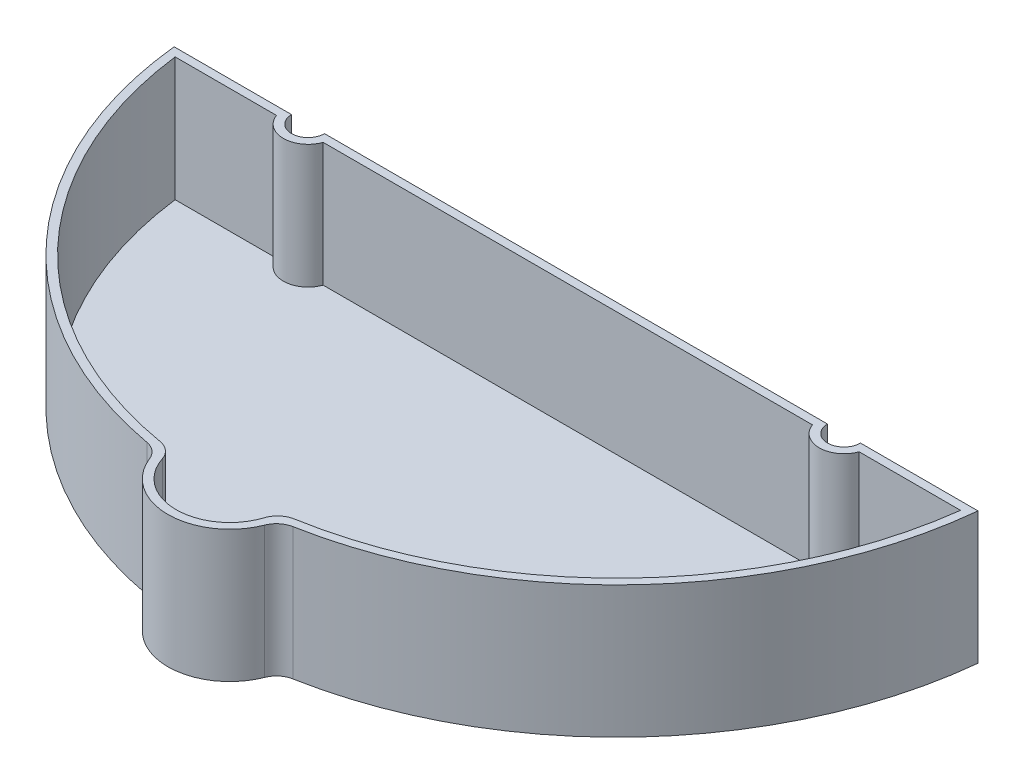
SolidWorks part; units mm, degrees
ref_plane "前视基准面" through (0, 0, 0) normal (0, 0, 1) x (1, 0, 0)
ref_plane "上视基准面" through (0, 0, 0) normal (0, 1, 0) x (1, 0, 0)
ref_plane "右视基准面" through (0, 0, 0) normal (1, 0, 0) x (0, 0, -1)
sketch "草图1" plane through (0, 0, 0) normal (0, 1, 0) x (1, 0, 0)
  line L0 (0, 0) -> (0, 54.022) construction
  line L1 (-97.4885, 50) -> (-69, 50)
  line L5 (-61, 50) -> (-7.5, 50)
  line L8 (7.5, 50) -> (61, 50)
  line L9 (69, 50) -> (97.4885, 50)
  line L10 (-7.5, 50) -> (7.5, 50)
  arc A2 (-97.4885, 50) -> (-14.7193, -36.8883) centre (0, 60) ccw
  arc A4 (-69, 50) -> (-61, 50) centre (-65, 50) ccw
  arc A6 (69, 50) -> (61, 50) centre (65, 50) cw
  arc A8 (-14.7193, -36.8883) -> (14.7193, -36.8883) centre (0, -34) ccw
  arc A9 (14.7193, -36.8883) -> (97.4885, 50) centre (0, 60) ccw
  point P1 (0, 0)
  dimension "D3" = 8
  dimension "D4" = 65
  dimension "D1" = 98
  dimension "D5" = 30
  dimension "D2" = 0
  dimension "D6" = 84
  dimension "D7" = 60
  dimension "D8" = 10
extrude "凸台-拉伸1" add sketch "草图1" along normal blind 32 from offset 2 offset against normal yes
shell "抽壳1" thickness 2
fillet "圆角1" radius 5 4 edges at (14.7193, 14, 36.8883) (-14.7193, 14, 36.8883) (12.9515, 15, 35.1223) (-12.9515, 15, 35.1223)
sketch "草图2" plane through (0, 30, 0) normal (0, 1, 0) x (1, 0, 0)
  line L0 (-97.4885, 50) -> (-69, 50)
  line L1 (-61, 50) -> (61, 50)
  line L2 (69, 50) -> (97.4885, 50)
  line L6 (63.0793, -15) -> (-63.0793, -15)
  line L7 (-69, 50) -> (-97.4885, 50) construction
  line L8 (0, 48) -> (0, -59.8527) construction
  line L9 (97.4885, 50) -> (69, 50) construction
  line L10 (61, 50) -> (-61, 50) construction
  arc A1 (-97.4885, 50) -> (-17.7151, -36.3856) centre (0, 60) ccw construction
  arc A2 (63.0793, -15) -> (97.4885, 50) centre (0, 60) ccw
  circle A8 centre (60.6593, 21.3431) radius 2.5
  arc A9 (-97.4885, 50) -> (-63.0793, -15) centre (0, 60) ccw
  arc A12 (61, 50) -> (69, 50) centre (65, 50) ccw
  arc A13 (-69, 50) -> (-61, 50) centre (-65, 50) ccw
  arc A15 (17.7151, -36.3856) -> (97.4885, 50) centre (0, 60) ccw construction
  arc A16 (-69, 50) -> (-61, 50) centre (-65, 50) ccw construction
  arc A17 (61, 50) -> (69, 50) centre (65, 50) ccw construction
  dimension "D2" = 5
  dimension "D1" = 15
sketch "草图3" plane through (0, -2, 0) normal (0, -1, 0) x (1, 0, 0)
  line L0 (0, 0) -> (0, -68.82) construction
  line L1 (0, 0) -> (-100.8554, 0) construction
  line L2 (61, -50) -> (-61, -50) construction
  line L3 (-37.5, -47) -> (37.5, -47)
  line L4 (-37.5, -47) -> (-37.5, -50)
  line L7 (37.5, -47) -> (37.5, -50)
  line L8 (37.5, -50) -> (-37.5, -50)
  line L9 (37.5, 15) -> (-37.5, 15)
  line L10 (-37.5, 18) -> (37.5, 18)
  line L11 (37.5, 18) -> (37.5, 15)
  line L12 (-37.5, 18) -> (-37.5, 15)
  circle A0 centre (40, -30) radius 5
  circle A1 centre (-40, -30) radius 5
  circle A2 centre (40, 0) radius 5
  circle A3 centre (-40, 0) radius 5
  point P8 (0, -50)
  point P9 (0, -50)
  dimension "D1" = 10
  dimension "D2" = 40
  dimension "D3" = 30
  dimension "D5" = 75
  dimension "D6" = 3
  dimension "D4" = 2
  dimension "D7" = 2
extrude "凸台-拉伸2" [suppressed] add sketch "草图3" along normal blind 3
